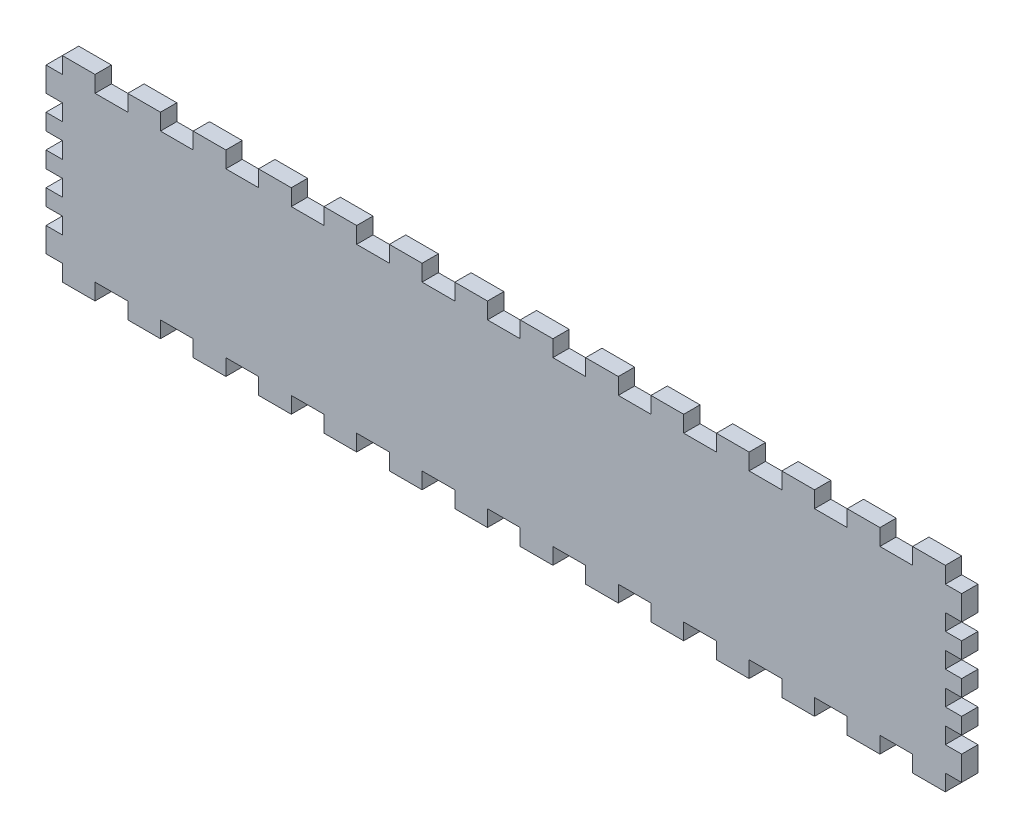
SolidWorks part; units mm, degrees
ref_plane "Front Plane" through (0, 0, 0) normal (0, 0, 1) x (1, 0, 0)
ref_plane "Top Plane" through (0, 0, 0) normal (0, 1, 0) x (1, 0, 0)
ref_plane "Right Plane" through (0, 0, 0) normal (1, 0, 0) x (0, 0, -1)
sketch "Sketch1" plane through (0, 0, 0) normal (0, 0, 1) x (1, 0, 0)
  line L1 (-177.8, -38.1) -> (177.8, -38.1)
  line L2 (-177.8, -38.1) -> (-177.8, 38.1)
  line L3 (-177.8, 38.1) -> (177.8, 38.1)
  line L4 (177.8, -38.1) -> (177.8, 38.1)
  line L5 (-177.8, -38.1) -> (177.8, 38.1) construction
  line L6 (-177.8, 38.1) -> (177.8, -38.1) construction
  point P0 (0, 0)
  dimension "D1" = 355.6
  dimension "D2" = 76.2
extrude "Boss-Extrude1" add sketch "Sketch1" along normal blind 6.35
sketch "Sketch2" plane through (0, 0, 0) normal (0, 0, 1) x (1, 0, 0)
  line L0 (177.8, -38.1) -> (177.8, 38.1) construction
  line L1 (158.75, -31.75) -> (146.05, -31.75)
  line L2 (158.75, -31.75) -> (158.75, -57.15)
  line L3 (158.75, -57.15) -> (146.05, -57.15)
  line L4 (146.05, -31.75) -> (146.05, -57.15)
  line L5 (158.75, -31.75) -> (146.05, -57.15) construction
  line L6 (158.75, -57.15) -> (146.05, -31.75) construction
  line L7 (-177.8, -38.1) -> (177.8, -38.1) construction
  point P0 (152.4, -44.45)
  dimension "D1" = 19.05
  dimension "D2" = 12.7
  dimension "D3" = 6.35
  dimension "D4" = 25.4
extrude "Cut-Extrude5" cut sketch "Sketch2" against normal through all and the other way through all contours L1 L4 L3 L2
pattern_linear "LPattern1" count 13 spacing 25.4 along (-1, 0, 0) of "Cut-Extrude5"
mirror "Mirror1" about plane through (0, 0, 0) normal (0, 1, 0) of "Cut-Extrude5", "LPattern1"
sketch "Sketch3" plane through (0, 0, 0) normal (0, 0, 1) x (1, 0, 0)
  line L0 (177.8, 38.1) -> (158.75, 38.1) construction
  line L1 (212.1985, 22.225) -> (171.45, 22.225)
  line L2 (212.1985, 22.225) -> (212.1985, 15.875)
  line L3 (212.1985, 15.875) -> (171.45, 15.875)
  line L4 (171.45, 22.225) -> (171.45, 15.875)
  line L5 (212.1985, 22.225) -> (171.45, 15.875) construction
  line L6 (212.1985, 15.875) -> (171.45, 22.225) construction
  line L7 (177.8, -38.1) -> (177.8, 38.1) construction
  line L8 (212.1985, 9.525) -> (171.45, 9.525)
  line L9 (212.1985, 9.525) -> (212.1985, 3.175)
  line L10 (212.1985, 3.175) -> (171.45, 3.175)
  line L11 (171.45, 9.525) -> (171.45, 3.175)
  line L12 (212.1985, 9.525) -> (171.45, 3.175) construction
  line L13 (212.1985, 3.175) -> (171.45, 9.525) construction
  line L14 (212.1985, -3.175) -> (171.45, -3.175)
  line L15 (212.1985, -3.175) -> (212.1985, -9.525)
  line L16 (212.1985, -9.525) -> (171.45, -9.525)
  line L17 (171.45, -3.175) -> (171.45, -9.525)
  line L18 (212.1985, -3.175) -> (171.45, -9.525) construction
  line L19 (212.1985, -9.525) -> (171.45, -3.175) construction
  line L20 (212.1985, -15.875) -> (171.45, -15.875)
  line L21 (212.1985, -15.875) -> (212.1985, -22.225)
  line L22 (212.1985, -22.225) -> (171.45, -22.225)
  line L23 (171.45, -15.875) -> (171.45, -22.225)
  line L24 (212.1985, -15.875) -> (171.45, -22.225) construction
  line L25 (212.1985, -22.225) -> (171.45, -15.875) construction
  line L27 (158.75, -38.1) -> (177.8, -38.1) construction
  line L28 (171.45, 57.15) -> (196.85, 57.15)
  line L29 (171.45, 57.15) -> (171.45, 31.75)
  line L30 (171.45, 31.75) -> (196.85, 31.75)
  line L31 (196.85, 57.15) -> (196.85, 31.75)
  line L32 (171.45, 57.15) -> (196.85, 31.75) construction
  line L33 (171.45, 31.75) -> (196.85, 57.15) construction
  line L34 (171.45, -31.75) -> (196.85, -31.75)
  line L35 (171.45, -31.75) -> (171.45, -57.15)
  line L36 (171.45, -57.15) -> (196.85, -57.15)
  line L37 (196.85, -31.75) -> (196.85, -57.15)
  line L38 (171.45, -31.75) -> (196.85, -57.15) construction
  line L39 (171.45, -57.15) -> (196.85, -31.75) construction
  point P0 (191.8242, 19.05)
  point P11 (191.8242, 6.35)
  point P16 (191.8242, -6.35)
  point P21 (191.8242, -19.05)
  point P26 (184.15, 44.45)
  point P31 (184.15, -44.45)
  dimension "D1" = 15.875
  dimension "D2" = 6.35
  dimension "D3" = 6.35
  dimension "D4" = 40.7485
  dimension "D6" = 15.875
  dimension "D7" = 6.35
  dimension "D8" = 6.35
  dimension "D9" = 25.4
  dimension "D10" = 25.4
  dimension "D11" = 6.35
  dimension "D12" = 6.35
  dimension "D13" = 25.4
  dimension "D14" = 25.4
  dimension "D5" = 4
extrude "Cut-Extrude7" cut sketch "Sketch3" along normal through all
mirror "Mirror2" about plane through (0, 0, 0) normal (1, 0, 0) of "Cut-Extrude7"
sketch "Sketch5" plane through (0, 0, 6.35) normal (0, 0, 1) x (1, 0, 0)
  line L0 (177.8, -31.75) -> (177.8, -22.225) construction
  line L1 (187.325, -31.75) -> (168.275, -31.75)
  line L2 (187.325, -31.75) -> (187.325, -57.15)
  line L3 (187.325, -57.15) -> (168.275, -57.15)
  line L4 (168.275, -31.75) -> (168.275, -57.15)
  line L5 (187.325, -31.75) -> (168.275, -57.15) construction
  line L6 (187.325, -57.15) -> (168.275, -31.75) construction
  line L7 (158.75, -38.1) -> (171.45, -38.1) construction
  line L8 (0, -3.4925) -> (0, 3.4925) construction
  line L9 (-187.325, -57.15) -> (-168.275, -31.75) construction
  line L10 (-187.325, -31.75) -> (-168.275, -57.15) construction
  line L11 (-168.275, -31.75) -> (-168.275, -57.15)
  line L12 (-187.325, -57.15) -> (-168.275, -57.15)
  line L13 (-187.325, -31.75) -> (-187.325, -57.15)
  line L14 (-187.325, -31.75) -> (-168.275, -31.75)
  point P0 (177.8, -44.45)
  point P15 (-177.8, -44.45)
  dimension "D1" = 9.525
  dimension "D2" = 6.35
  dimension "D3" = 25.4
extrude "Cut-Extrude8" [suppressed] cut sketch "Sketch5" against normal through all
mirror "Mirror3" [suppressed] about plane through (0, 0, 0) normal (0, 1, 0)
